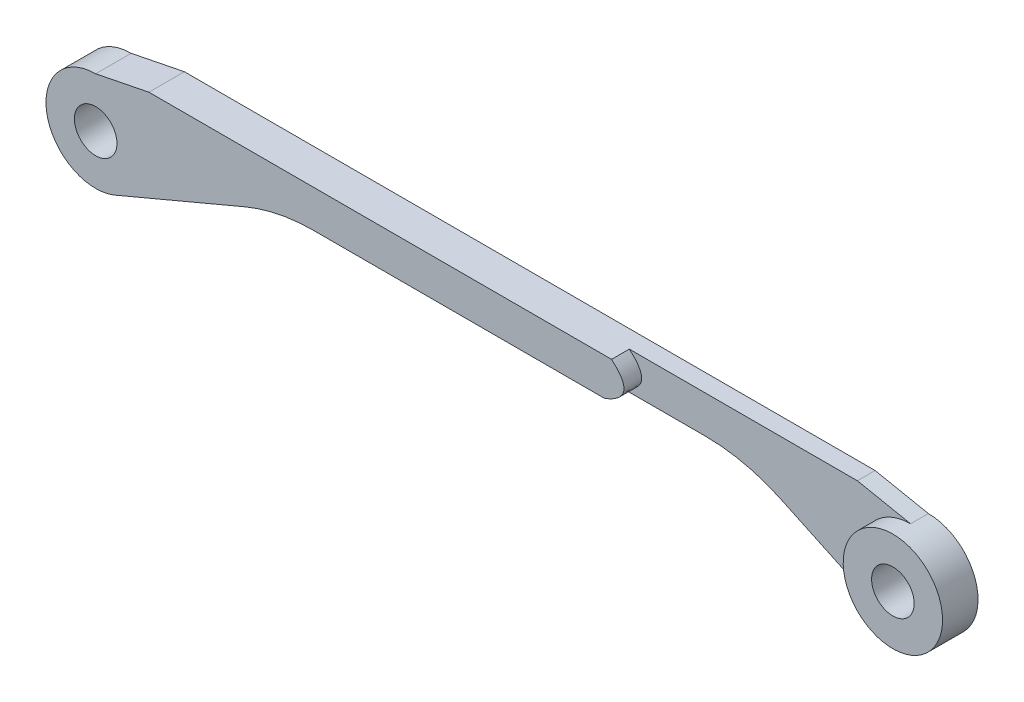
SolidWorks part; units mm, degrees
ref_plane "前视基准面" through (0, 0, 0) normal (0, 0, 1) x (1, 0, 0)
ref_plane "上视基准面" through (0, 0, 0) normal (0, 1, 0) x (1, 0, 0)
ref_plane "右视基准面" through (0, 0, 0) normal (1, 0, 0) x (0, 0, -1)
sketch "草图1" plane through (0, 0, 0) normal (0, 0, 1) x (1, 0, 0)
  line L0 (0, 0) -> (-224.65, 0) construction
  line L1 (-112.325, 0) -> (-112.325, 17)
  line L2 (-209.65, 17) -> (-15, 17)
  line L3 (-209.65, 17) -> (-224.65, 14)
  line L4 (-15, 17) -> (0, 14)
  line L5 (-224.65, 0) -> (-200.5019, 6.4705)
  line L6 (-173.3188, 6.4705) -> (-219.2058, -12.8981)
  line L7 (-46.6812, 6.4705) -> (-5.9549, -12.6704)
  line L8 (0, 0) -> (-24.1481, 6.4705)
  line L9 (-200.5019, 6.4705) -> (-24.1481, 6.4705)
  circle A0 centre (0, 0) radius 6
  circle A1 centre (-224.65, 0) radius 6
  circle A2 centre (-224.65, 0) radius 14
  circle A3 centre (0, 0) radius 14
  point P10 (-112.325, 17)
  dimension "D1" = 28
  dimension "D2" = 28
  dimension "D7" = 12
  dimension "D8" = 12
  dimension "D3" = 224.65
  dimension "D4" = 15
  dimension "D5" = 15
  dimension "D6" = 25
extrude "凸台-拉伸1" add sketch "草图1" along normal blind 10
fillet "圆角1" radius 50 2 edges at (-46.6812, 6.4705, 5) (-173.3188, 6.4705, 5)
sketch "草图2" plane through (0, 0, 0) normal (0, 0, -1) x (-1, 0, 0)
  line L0 (209.65, 17) -> (15, 17) construction
  line L1 (163.1988, 6.4705) -> (57.8451, 6.4705) construction
  line L11 (5.9549, -12.6704) -> (36.5775, 1.7219)
  line L20 (57.8451, 6.4705) -> (163.1988, 6.4705)
  line L21 (182.6423, 2.5351) -> (219.2058, -12.8981)
  line L22 (224.65, 14) -> (209.65, 17)
  line L23 (209.65, 17) -> (15, 17)
  line L24 (15, 17) -> (0, 14)
  line L25 (5.9549, -12.6704) -> (36.5775, 1.7219)
  line L26 (57.8451, 6.4705) -> (163.1988, 6.4705)
  line L27 (182.6423, 2.5351) -> (219.2058, -12.8981)
  line L28 (224.65, 14) -> (209.65, 17)
  line L29 (209.65, 17) -> (15, 17)
  line L30 (15, 17) -> (0, 14)
  arc A13 (57.8451, 6.4705) -> (36.5775, 1.7219) centre (57.8451, -43.5295) ccw
  arc A14 (182.6423, 2.5351) -> (163.1988, 6.4705) centre (163.1988, -43.5295) ccw
  arc A15 (219.2058, -12.8981) -> (224.65, 14) centre (224.65, 0) ccw
  arc A16 (0, 14) -> (5.9549, -12.6704) centre (0, 0) ccw
  arc A17 (57.8451, 6.4705) -> (36.5775, 1.7219) centre (57.8451, -43.5295) ccw
  arc A18 (182.6423, 2.5351) -> (163.1988, 6.4705) centre (163.1988, -43.5295) ccw
  arc A19 (219.2058, -12.8981) -> (224.65, 14) centre (224.65, 0) ccw
  arc A20 (0, 14) -> (5.9549, -12.6704) centre (0, 0) ccw
  spline S0 degree 2 poles (79.2716, 17) (71.4035, 10.2559) (81.2732, 6.4705) knots 0 0 0 1 1 1
  line M11 (5.9549, -12.6704) -> (36.5775, 1.7219)
  line M19 (15, 17) -> (0, 14)
  arc M20 (0, 14) -> (5.9549, -12.6704) centre (0, 0) ccw
  circle M21 centre (0, 0) radius 6
  dimension "D1" = 0
extrude "切除-拉伸1" cut sketch "草图2" along normal blind 5 from surface at -10 contours S0 M19 M20 M11 M21
sketch "草图3" plane through (0, 0, 5) normal (0, 0, 1) x (1, 0, 0)
  line L3 (-15, 17) -> (-79.2716, 17)
  line L4 (-36.5775, 1.7219) -> (-5.9549, -12.6704)
  line L5 (0, 14) -> (-15, 17)
  line L6 (-15, 17) -> (-79.2716, 17)
  line L7 (-36.5775, 1.7219) -> (-5.9549, -12.6704)
  line L8 (0, 14) -> (-15, 17)
  line L10 (-81.2732, 6.4705) -> (-57.8451, 6.4705)
  line L11 (-81.2732, 6.4705) -> (-57.8451, 6.4705)
  circle A0 centre (0, 0) radius 14
  circle A1 centre (0, 0) radius 6
  arc A4 (-36.5775, 1.7219) -> (-57.8451, 6.4705) centre (-57.8451, -43.5295) ccw
  arc A5 (-5.9549, -12.6704) -> (0, 14) centre (0, 0) ccw
  arc A7 (-36.5775, 1.7219) -> (-57.8451, 6.4705) centre (-57.8451, -43.5295) ccw
  arc A8 (-5.9549, -12.6704) -> (0, 14) centre (0, 0) ccw
  parabola Q1 (-79.2716, 17) -> (-81.2732, 6.4705) focus (-77.3998, 11.3292) apex (-75.8253, 11.0665)
  parabola Q2 (-79.2716, 17) -> (-81.2732, 6.4705) focus (-77.3998, 11.3292) apex (-75.8253, 11.0665)
  circle M7 centre (0, 0) radius 6
  arc M12 (-5.9549, -12.6704) -> (0, 14) centre (0, 0) ccw
  dimension "D2" = 12
  dimension "D1" = 0
extrude "凸台-拉伸2" add sketch "草图3" along normal blind 5 contours A0 M12 M7
